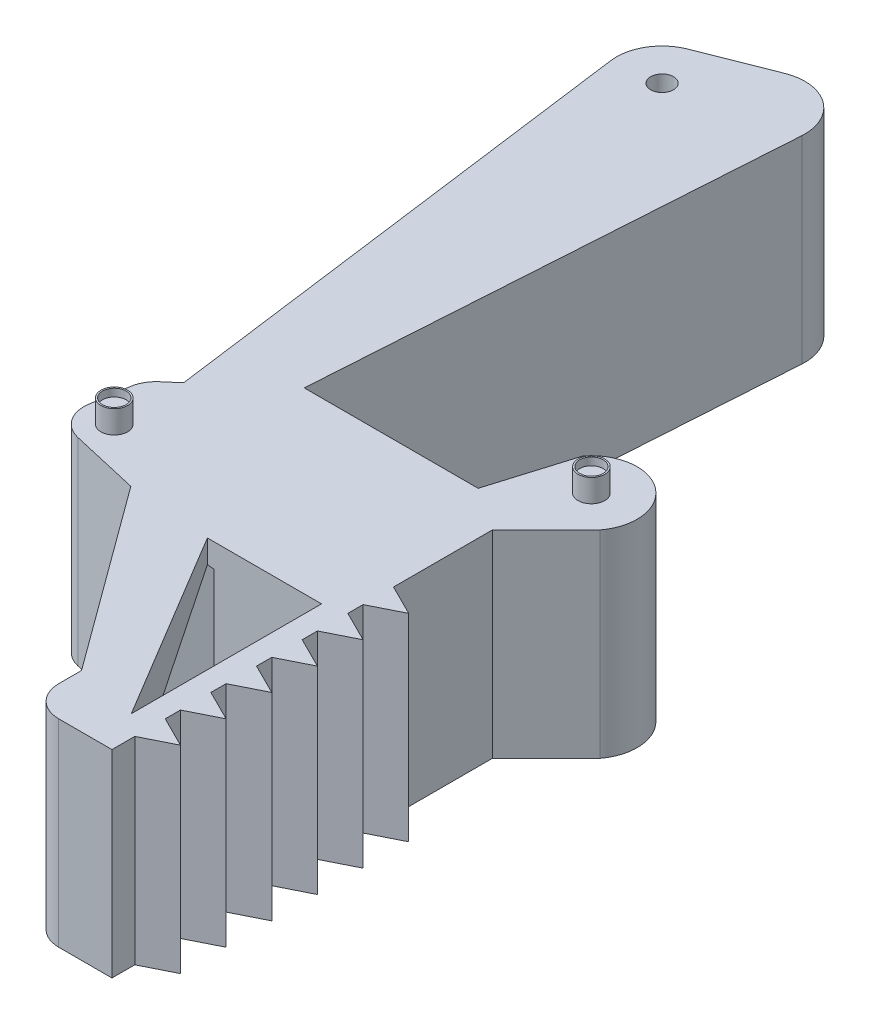
SolidWorks part; units mm, degrees
ref_plane "Front Plane" through (0, 0, 0) normal (0, 0, 1) x (1, 0, 0)
ref_plane "Top Plane" through (0, 0, 0) normal (0, 1, 0) x (1, 0, 0)
ref_plane "Right Plane" through (0, 0, 0) normal (1, 0, 0) x (0, 0, -1)
sketch "Sketch1" plane through (0, 0, 0) normal (0, 1, 0) x (1, 0, 0)
  line L0 (0, 0) -> (-134.3718, 0) construction
  line L1 (-59.2437, -78.1875) -> (-68.4594, -8.7968)
  line L2 (-68.4594, -8.7968) -> (-46.1297, 0)
  line L3 (-46.1297, 0) -> (-50.7316, -70.8507)
  line L4 (-50.7316, -70.8507) -> (-59.2437, -78.1875)
  line L5 (-50.7316, -70.8507) -> (-62.0935, -80.6439)
  line L6 (-62.0935, -80.6439) -> (-63.5968, -90.5303)
  line L7 (-63.5968, -90.5303) -> (-50.9274, -93.4432)
  line L8 (-50.9274, -93.4432) -> (-33.2027, -117.6473)
  line L9 (-33.2027, -117.6473) -> (-33.2027, -124.6473)
  line L10 (-33.2027, -124.6473) -> (-22.2027, -124.6473)
  line L11 (-22.2027, -124.6473) -> (-22.2027, -74.6473)
  line L12 (-22.2027, -74.6473) -> (-15.1316, -67.5762)
  line L13 (-50.7316, -70.8507) -> (-27.8766, -70.8507)
  line L14 (-27.8766, -70.8507) -> (-24.6739, -60.2998)
  arc A0 (-24.6739, -60.2998) -> (-15.1316, -67.5762) centre (-19.9027, -63.938) cw
  dimension "D1" = 70
  dimension "D2" = 71
  dimension "D3" = 24
  dimension "D4" = 11.2376
  dimension "D5" = 15
  dimension "D6" = 10
  dimension "D7" = 13
  dimension "D8" = 30
  dimension "D9" = 7
  dimension "D10" = 11
  dimension "D11" = 50
  dimension "D12" = 10
extrude "Boss-Extrude1" add sketch "Sketch1" along normal blind 26 contours A0 L14 L13 L4 L5 L6 L7 L8 L9 L10 L11 L12 | L4 L3 L2 L1
fillet "Fillet1" radius 6 2 edges at (-46.1297, 13, 0) (-68.4594, 13, 8.7968)
fillet "Fillet2" radius 4 3 edges at (-33.2027, 13, 124.6473) (-63.5968, 13, 90.5303) (-62.0935, 13, 80.6439)
sketch "Sketch2" plane through (0, 26, 0) normal (0, 1, 0) x (1, 0, 0)
  line L0 (-22.2027, -124.6473) -> (-22.2027, -119.6473)
  line L1 (-22.2027, -124.6473) -> (-22.2027, -74.6473) construction
  line L2 (-22.2027, -119.6473) -> (-18.2027, -119.6473) construction
  line L3 (-22.2027, -117.6473) -> (-22.2027, -121.6473)
  line L4 (-22.2027, -117.6473) -> (-18.2027, -119.6473)
  line L5 (-18.2027, -119.6473) -> (-22.2027, -121.6473)
  point P9 (-22.2027, -119.6473)
  line M7 (-22.2027, -124.6473) -> (-22.2027, -74.6473)
  dimension "D1" = 4
  dimension "D2" = 5
  dimension "D3" = 4
extrude "Boss-Extrude2" add sketch "Sketch2" against normal blind 26 contours L2 L0 L5 | L2 L4 M7
pattern_linear "LPattern1" count 6 spacing 6 along (0, 0, -1) of "Boss-Extrude2"
sketch "Sketch3" plane through (0, 26, 0) normal (0, 1, 0) x (1, 0, 0)
  line L0 (-25.0142, -119.2928) -> (-25.0142, -94.2928)
  line L1 (-25.0142, -94.2928) -> (-40.0142, -94.2928)
  line L2 (-40.0142, -94.2928) -> (-25.0142, -119.2928)
  dimension "D1" = 15
  dimension "D2" = 25
extrude "Cut-Extrude1" cut sketch "Sketch3" against normal through all
sketch "Sketch4" plane through (-77.6923, 0, 56.8941) normal (-0.8068, 0, 0.5908) x (0.5908, 0, 0.8068)
  line L0 (52.3011, 23) -> (52.3011, 4.0951)
  line L1 (52.3011, 4.0951) -> (70.3011, 8.2733)
  line L2 (70.3011, 8.2733) -> (70.3011, 19.5752)
  line L3 (52.3011, 23) -> (70.3011, 19.5752)
  line L4 (45.3011, 26) -> (75.3011, 26) construction
  line L5 (75.3011, 26) -> (75.3011, 0) construction
  line L6 (45.3011, 26) -> (45.3011, 0) construction
  dimension "D1" = 3
  dimension "D2" = 5
  dimension "D3" = 7
extrude "Cut-Extrude2" cut sketch "Sketch4" against normal blind 9
sketch "Sketch5" plane through (0, 26, 0) normal (0, 1, 0) x (1, 0, 0)
  circle A0 centre (-61.8938, -12.6591) radius 1.5
  dimension "D1" = 3
extrude "Cut-Extrude3" cut sketch "Sketch5" against normal through all
sketch "Sketch6" plane through (0, 26, 0) normal (0, 1, 0) x (1, 0, 0)
  circle A0 centre (-59.0845, -87.4634) radius 1.75
  circle A1 centre (-19.9027, -63.938) radius 1.75
  dimension "D1" = 3.5
  dimension "D2" = 3.5
extrude "Boss-Extrude4" add sketch "Sketch6" along normal blind 3
sketch "Sketch7" plane through (0, 29, 0) normal (0, 1, 0) x (1, 0, 0)
  circle A2 centre (-59.0845, -87.4634) radius 1.55
  circle A3 centre (-59.0845, -87.4634) radius 1.55
  dimension "D1" = 0.2
extrude "Cut-Extrude4" cut sketch "Sketch7" against normal blind 1
sketch "Sketch8" plane through (0, 29, 0) normal (0, 1, 0) x (1, 0, 0)
  circle A0 centre (-19.9027, -63.938) radius 1.55
  circle A1 centre (-19.9027, -63.938) radius 1.75
  circle A2 centre (-19.9027, -63.938) radius 1.75
  dimension "D1" = 0
  dimension "D2" = 0.2
extrude "Cut-Extrude9" cut sketch "Sketch8" against normal blind 1 contours A0
